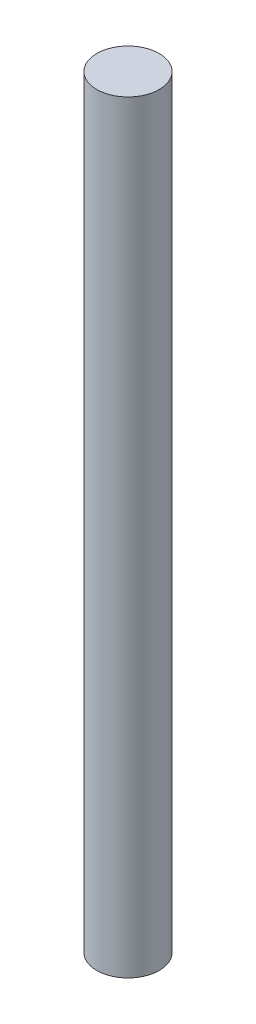
SolidWorks part; units mm, degrees
ref_plane "Front Plane" through (0, 0, 0) normal (0, 0, 1) x (1, 0, 0)
ref_plane "Top Plane" through (0, 0, 0) normal (0, 1, 0) x (1, 0, 0)
ref_plane "Right Plane" through (0, 0, 0) normal (1, 0, 0) x (0, 0, -1)
sketch "Sketch1" plane through (0, 0, 0) normal (0, 0, 1) x (1, 0, 0)
  line L0 (0, 0) -> (0, 165)
  point P6 (0, 165)
  dimension "D2" = 165
sketch "Sketch2" plane through (0, 0, 0) normal (0, 1, 0) x (1, 0, 0)
  circle A0 centre (0, 0) radius 6.75
  dimension "D1" = 13.5
sweep "Sweep1" add profiles "Sketch2" path "Sketch1"
